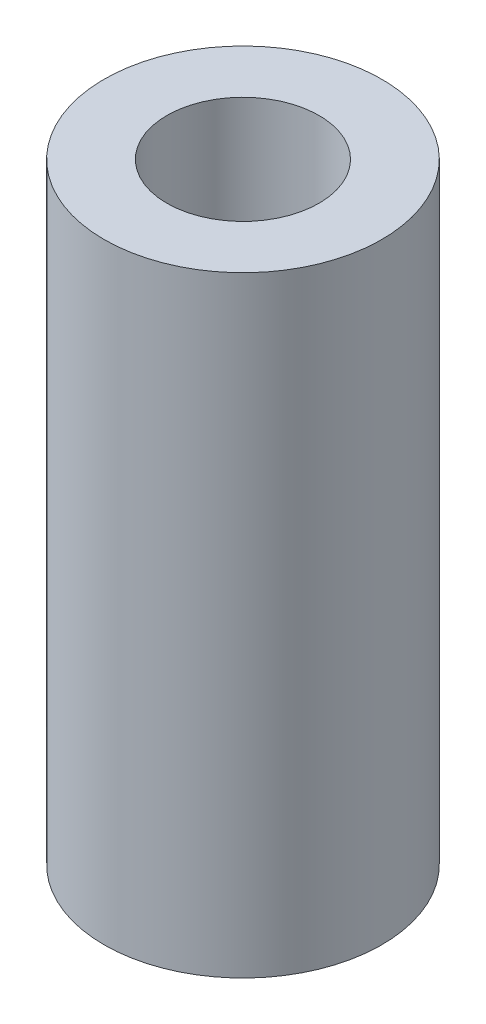
SolidWorks part; units mm, degrees
ref_plane "Front Plane" through (0, 0, 0) normal (0, 0, 1) x (1, 0, 0)
ref_plane "Top Plane" through (0, 0, 0) normal (0, 1, 0) x (1, 0, 0)
ref_plane "Right Plane" through (0, 0, 0) normal (1, 0, 0) x (0, 0, -1)
sketch "Sketch1" plane through (0, 0, 0) normal (0, 1, 0) x (1, 0, 0)
  circle A0 centre (0, 0) radius 6.35
  arc A4 (5.6286, -2.9396) -> (-4.0286, 4.9085) centre (0, 0) ccw construction
  circle A5 centre (0, 0) radius 3.4798
  circle A6 centre (0, 0) radius 3.4798
  dimension "D1" = 0.0508
extrude "Boss-Extrude1" add sketch "Sketch1" along normal up to surface (27.9373 mm away)
